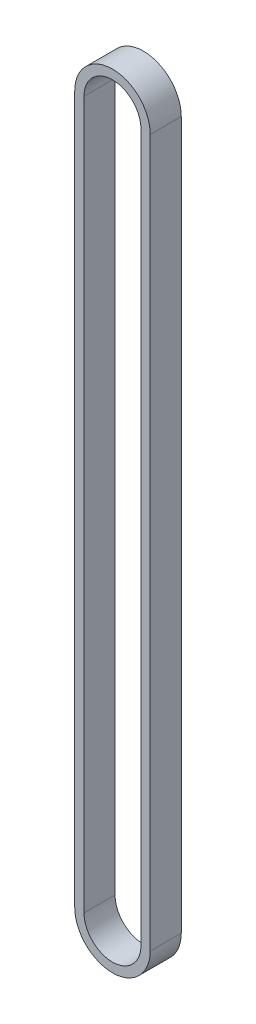
SolidWorks part; units mm, degrees
material "天然橡胶"
ref_plane "前视基准面" through (0, 0, 0) normal (0, 0, 1) x (1, 0, 0)
ref_plane "上视基准面" through (0, 0, 0) normal (0, 1, 0) x (1, 0, 0)
ref_plane "右视基准面" through (0, 0, 0) normal (1, 0, 0) x (0, 0, -1)
other "Configuration Table"
sketch "草图1" plane through (0, 0, 0) normal (0, 0, 1) x (1, 0, 0)
  line L0 (0, -114) -> (0, 114) construction
  line L1 (-9.17, -114) -> (-9.17, 114)
  line L2 (9.17, -114) -> (9.17, 114)
  line L3 (-12.17, -114) -> (-12.17, 114)
  line L4 (12.17, -114) -> (12.17, 114)
  arc A0 (-9.17, -114) -> (9.17, -114) centre (0, -114) ccw
  arc A1 (9.17, 114) -> (-9.17, 114) centre (0, 114) ccw
  arc A2 (12.17, 114) -> (-12.17, 114) centre (0, 114) ccw
  arc A3 (-12.17, -114) -> (12.17, -114) centre (0, -114) ccw
  point P2 (0, 0)
  dimension "D2" = 9.17
  dimension "D1" = 228
  dimension "D3" = 3
extrude "凸台-拉伸1" add sketch "草图1" along normal blind 10
